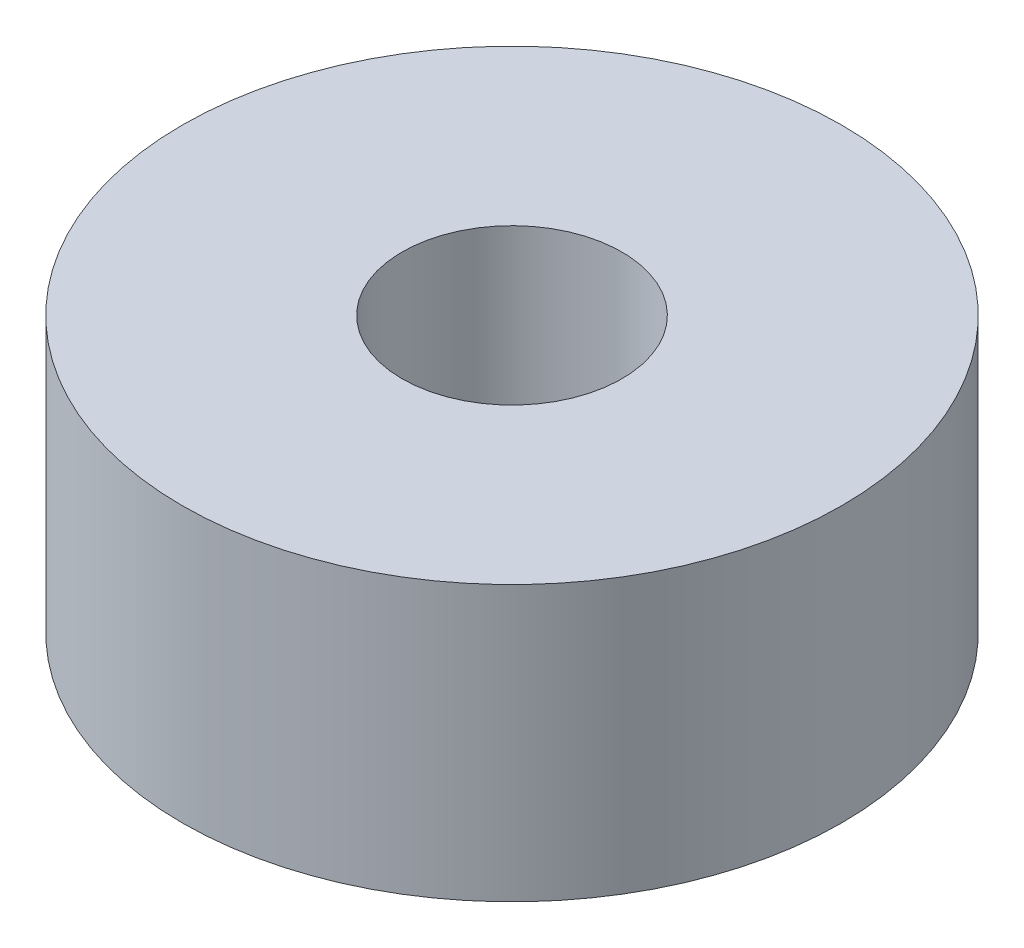
SolidWorks part; units mm, degrees
ref_plane "Front Plane" through (0, 0, 0) normal (0, 0, 1) x (1, 0, 0)
ref_plane "Top Plane" through (0, 0, 0) normal (0, 1, 0) x (1, 0, 0)
ref_plane "Right Plane" through (0, 0, 0) normal (1, 0, 0) x (0, 0, -1)
sketch "Sketch1" plane through (0, 0, 0) normal (0, 1, 0) x (1, 0, 0)
  circle A0 centre (0, 0) radius 3
  circle A1 centre (0, 0) radius 1
  dimension "D1" = 6
  dimension "D2" = 2
extrude "Boss-Extrude1" add sketch "Sketch1" along normal blind 2.5
